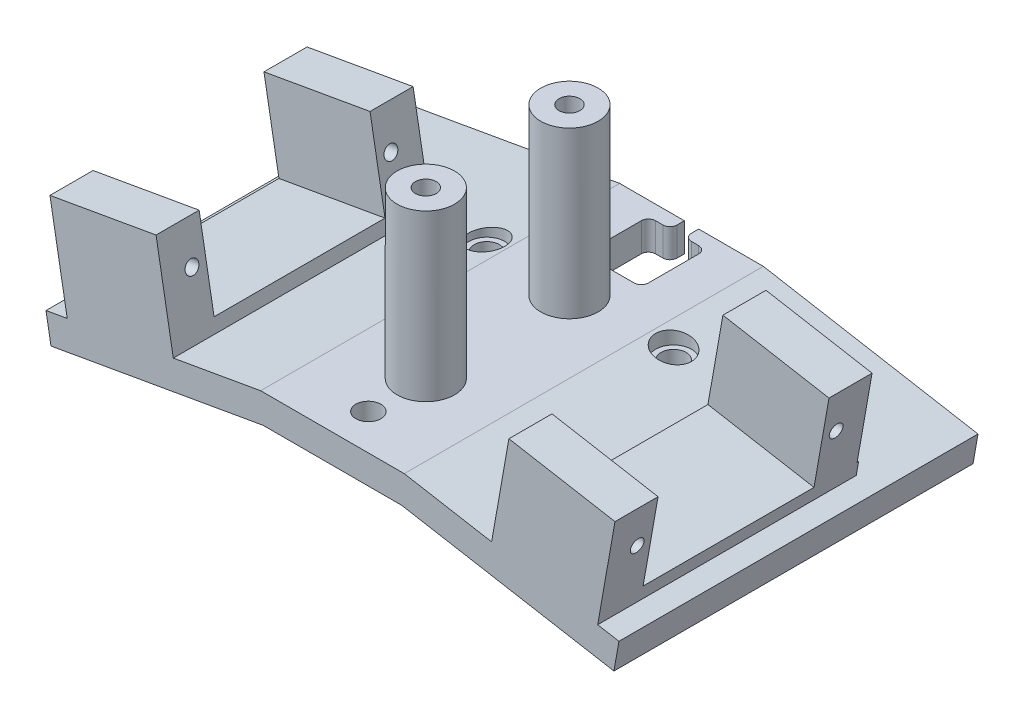
SolidWorks part; units mm, degrees
ref_plane "前视基准面" through (0, 0, 0) normal (0, 0, 1) x (1, 0, 0)
ref_plane "上视基准面" through (0, 0, 0) normal (0, 1, 0) x (1, 0, 0)
ref_plane "右视基准面" through (0, 0, 0) normal (1, 0, 0) x (0, 0, -1)
other "Configuration Table"
sketch "草图1" plane through (0, 0, 0) normal (0, 0, 1) x (1, 0, 0)
  line L0 (0, 0) -> (9.65, 0)
  line L1 (9.65, 0) -> (39.1943, -5.2094)
  line L2 (39.1943, -5.2094) -> (39.8889, -1.2702)
  line L3 (39.8889, -1.2702) -> (10, 4)
  line L4 (10, 4) -> (0, 4)
  line L5 (0, 4) -> (0, 0)
  dimension "D1" = 4
  dimension "D2" = 30
  dimension "D3" = 10
  dimension "D4" = 4
  dimension "D5" = 190
extrude "凸台-拉伸1" add sketch "草图1" along normal mid plane 50
sketch "草图2" plane through (0, 0, 25) normal (0, 0, 1) x (1, 0, 0)
  line L0 (22.1623, 1.8555) -> (22.4836, 3.6773)
  line L1 (39.8889, -1.2702) -> (10, 4) construction
  line L2 (22.4836, 3.6773) -> (37.2557, 1.0726)
  line L3 (37.2557, 1.0726) -> (36.9344, -0.7493)
  line L4 (36.9344, -0.7493) -> (22.1623, 1.8555)
  line L5 (39.1943, -5.2094) -> (39.8889, -1.2702) construction
  dimension "D1" = 1.85
  dimension "D2" = 18
  dimension "D3" = 15
extrude "凸台-拉伸2" add sketch "草图2" against normal blind 36
sketch "草图3" plane through (1.3068, 7.4114, 0) normal (0.1736, 0.9848, 0) x (0.9848, -0.1736, 0)
  line L0 (36.5034, 11) -> (36.5034, -25) construction
  line L1 (21.5034, -19) -> (36.5034, -19)
  line L2 (21.5034, -19) -> (21.5034, -25)
  line L3 (21.5034, -25) -> (36.5034, -25)
  line L4 (36.5034, -19) -> (36.5034, -25)
  line L5 (21.5034, 11) -> (21.5034, -25) construction
  line L6 (36.5034, 11) -> (36.5034, -25) construction
  line L7 (21.5034, 10.8) -> (36.5034, 10.8)
  line L8 (21.5034, 10.8) -> (21.5034, 4.8)
  line L9 (21.5034, 4.8) -> (36.5034, 4.8)
  line L10 (36.5034, 10.8) -> (36.5034, 4.8)
  line L11 (39.5034, -25) -> (36.5034, -25) construction
  dimension "D1" = 6
  dimension "D2" = 6
  dimension "D3" = 23.8
extrude "凸台-拉伸3" add sketch "草图3" along normal blind 12
sketch "草图4" plane through (35.9489, -6.3388, 0) normal (0.9848, -0.1736, 0) x (0, 0, -1)
  line L0 (4.8, 7.5257) -> (-19, 7.5257) construction
  line L1 (-19, 19.5257) -> (-19, 7.5257) construction
  line L2 (4.8, 19.5257) -> (4.8, 7.5257) construction
  circle A0 centre (-20.95, 14.0257) radius 0.95
  circle A1 centre (6.75, 14.0257) radius 0.95
  dimension "D1" = 6.5
  dimension "D2" = 6.5
  dimension "D3" = 1.95
  dimension "D4" = 1.95
  dimension "D5" = 1.9
  dimension "D6" = 1.9
extrude "切除-拉伸1" cut sketch "草图4" against normal blind 21
mirror "镜向1" about plane through (0, 0, 0) normal (1, 0, 0) of "切除-拉伸1", "凸台-拉伸3", "凸台-拉伸2", "凸台-拉伸1"
sketch "草图5" plane through (0, 4, 0) normal (0, 1, 0) x (1, 0, 0)
  circle A0 centre (0, -12) radius 4
  circle A1 centre (0, 8) radius 4
  circle A2 centre (0, 8) radius 1.45
  circle A3 centre (0, -12) radius 1.45
  dimension "D2" = 12
  dimension "D3" = 8
  dimension "D4" = 8
  dimension "D5" = 2.9
  dimension "D6" = 2.9
  dimension "D1" = 20
extrude "凸台-拉伸4" add sketch "草图5" along normal blind 23
sketch "草图6" plane through (0, 4, 0) normal (0, 1, 0) x (1, 0, 0)
  circle A0 centre (0, -20) radius 1.75
  circle A1 centre (-13, 9.5) radius 1.75
  circle A2 centre (13, 9.5) radius 1.75
  dimension "D1" = 20
  dimension "D2" = 26
  dimension "D3" = 29.5
  dimension "D4" = 3.5
  dimension "D5" = 13
extrude "切除-拉伸2" cut sketch "草图6" against normal blind 20
sketch "草图7" plane through (0, 4, 0) normal (0, 1, 0) x (1, 0, 0)
  circle A0 centre (-13, 9.5) radius 2.5
  circle A1 centre (13, 9.5) radius 2.5
  circle A2 centre (13, 9.5) radius 1.75 construction
  dimension "D1" = 5
extrude "切除-拉伸3" cut sketch "草图7" against normal blind 2
sketch "草图8" plane through (0, 4, 0) normal (0, 1, 0) x (1, 0, 0)
  line L0 (10, 25) -> (-10, 25) construction
  line L1 (-4, 23) -> (-1, 23)
  line L2 (-4, 23) -> (-4, 14)
  line L3 (-4, 14) -> (4, 14)
  line L4 (4, 23) -> (4, 14)
  line L5 (-4, 23) -> (4, 14) construction
  line L6 (-4, 14) -> (4, 23) construction
  line L7 (-1, 25) -> (1, 25)
  line L8 (-1, 25) -> (-1, 23)
  line L10 (1, 25) -> (1, 23)
  line L11 (1, 23) -> (4, 23)
  point P0 (0, 18.5)
  point P12 (0, 25)
  dimension "D1" = 8
  dimension "D2" = 9
  dimension "D3" = 14
  dimension "D4" = 2
extrude "切除-拉伸4" cut sketch "草图8" against normal through all
fillet "圆角4" radius 1 6 edges at (4, 2, -23) (-4, 2, -23) (1, 2, -23) (-1, 2, -23) (-4, 2, -14) (4, 2, -14)
